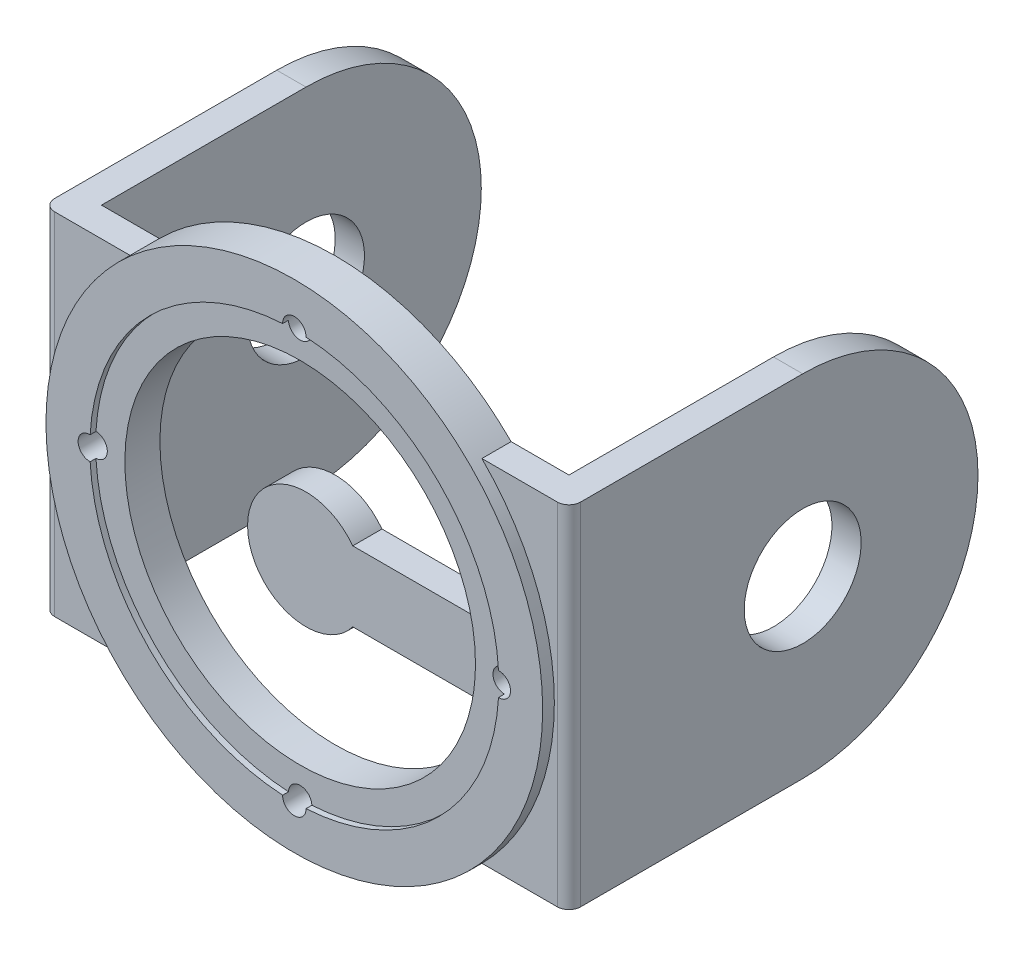
SolidWorks part; units mm, degrees
ref_plane "前视" through (0, 0, 0) normal (0, 0, 1) x (1, 0, 0)
ref_plane "上视" through (0, 0, 0) normal (0, 1, 0) x (1, 0, 0)
ref_plane "右视" through (0, 0, 0) normal (1, 0, 0) x (0, 0, -1)
sketch "草图1" plane through (0, 0, 0) normal (0, 0, 1) x (1, 0, 0)
  line L0 (-30.104, -30) -> (-40, -30)
  line L1 (40, -30) -> (30.104, -30)
  line L2 (40, -30) -> (40, 30)
  line L3 (40, 30) -> (30.104, 30)
  line L4 (-40, -30) -> (-40, 30)
  line L5 (40, -30) -> (-40, 30) construction
  line L6 (40, 30) -> (-40, -30) construction
  line L7 (-30.104, 30) -> (-40, 30)
  circle A0 centre (0, 0) radius 30
  arc A1 (-30.104, -30) -> (30.104, -30) centre (0, 0) ccw
  arc A2 (30.104, 30) -> (-30.104, 30) centre (0, 0) ccw
  point P0 (0, 0)
  dimension "D3" = 60
  dimension "D4" = 85
  dimension "D1" = 80
  dimension "D2" = 60
extrude "凸台-拉伸1" add sketch "草图1" along normal blind 5
sketch "草图2" plane through (0, 0, 5) normal (0, 0, 1) x (1, 0, 0)
  circle A0 centre (0, 0) radius 30
  circle A1 centre (0, 0) radius 35
  dimension "D1" = 70
extrude "凸台-拉伸2" add sketch "草图2" along normal blind 1
sketch "草图4" plane through (0, 0, 5) normal (0, 0, 1) x (1, 0, 0)
  circle A0 centre (0, 0) radius 35
  circle A1 centre (0, 0) radius 42.5
  dimension "D1" = 85
extrude "凸台-拉伸3" add sketch "草图4" along normal blind 2
sketch "草图5" plane through (0, 0, 0) normal (0, 0, -1) x (-1, 0, 0)
  line L0 (-40, 0) -> (40, 0) construction
  line L1 (-40, -30) -> (-40, 30) construction
  line L2 (40, 30) -> (40, -30) construction
  line L3 (0, 42.5) -> (0, -42.5) construction
  arc A0 (30.104, 30) -> (-30.104, 30) centre (0, 0) ccw construction
  arc A1 (-30.104, -30) -> (30.104, -30) centre (0, 0) ccw construction
  circle A2 centre (0, 35) radius 2
  circle A3 centre (35, 0) radius 2
  circle A4 centre (0, -35) radius 2
  circle A5 centre (-35, 0) radius 2
  point P27 (0, 0)
  dimension "D2" = 4
  dimension "D1" = 35
  dimension "D3" = 4
extrude "切除-拉伸3" cut sketch "草图5" against normal through all
sketch "草图6" plane through (-40, 0, 0) normal (-1, 0, 0) x (0, 0, 1)
  line L1 (5, -30) -> (-35, -30)
  line L2 (5, -30) -> (5, 30)
  line L3 (5, 30) -> (-35, 30)
  arc A0 (-35, 30) -> (-35, -30) centre (-35, 0) ccw
  circle A1 centre (-35, 0) radius 10
  dimension "D3" = 20
  dimension "D1" = 60
  dimension "D2" = 40
extrude "凸台-拉伸4" add sketch "草图6" along normal blind 5
fillet "圆角1" radius 2 1 edges at (-45, 0, 5)
mirror "镜向1" about plane through (0, 0, 0) normal (1, 0, 0) of "凸台-拉伸4", "圆角1"
sketch "草图7" plane through (0, 0, 0) normal (0, 0, -1) x (-1, 0, 0)
  line L0 (-30.2865, 0) -> (10, 0) construction
  line L3 (-8, -6) -> (-29.6862, -6)
  line L4 (-8, 6) -> (-29.6862, 6)
  arc A0 (-29.6862, 6) -> (-29.6862, -6) centre (0, 0) ccw
  arc A1 (-8, -6) -> (-8, 6) centre (0, 0) ccw
  dimension "D1" = 20
  dimension "D2" = 6
extrude "凸台-拉伸5" add sketch "草图7" against normal blind 5
